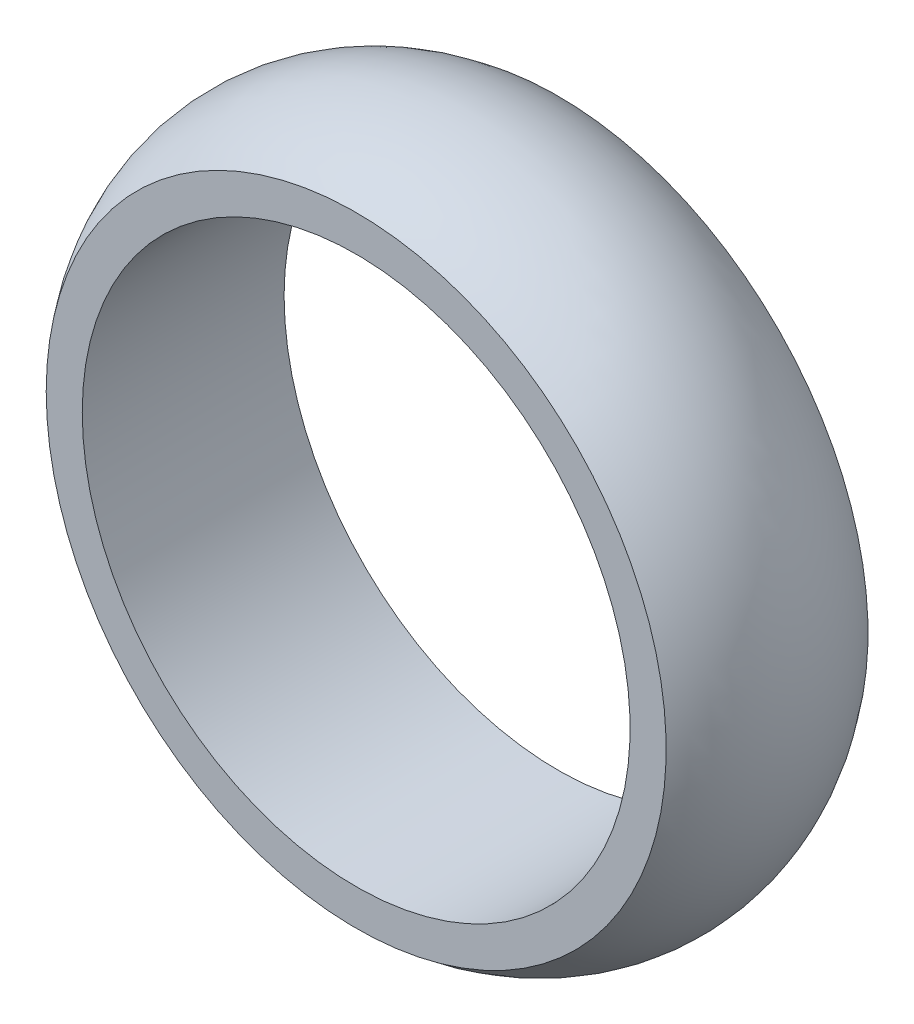
SolidWorks part; units mm, degrees
material "Nylon 101"
ref_plane "Спереди" through (0, 0, 0) normal (0, 0, 1) x (1, 0, 0)
ref_plane "Сверху" through (0, 0, 0) normal (0, 1, 0) x (1, 0, 0)
ref_plane "Справа" through (0, 0, 0) normal (1, 0, 0) x (0, 0, -1)
other "Configuration Table"
sketch "Sketch1" plane through (0, 0, 0) normal (0, 1, 0) x (1, 0, 0)
  line L0 (-15.042, 0) -> (17.2502, 0) construction
  line L1 (-9.5, 3.5) -> (-10.75, 3.5)
  line L2 (-9.5, 3.5) -> (-9.5, -3.5)
  line L3 (-9.5, -3.5) -> (-10.75, -3.5)
  line L4 (0, 8.7081) -> (0, -13.7539) construction
  line L5 (-10.75, 6.5523) -> (-10.75, 1.6241) construction
  arc A0 (-10.75, -3.5) -> (-10.75, 3.5) centre (-6.475, 0) cw
  dimension "D1" = 24
  dimension "D4" = 1.25
  dimension "D5" = 1.25
  dimension "D2" = 7
  dimension "D3" = 19
revolve "Revolve1" add sketch "Sketch1" angle 360 about L4
